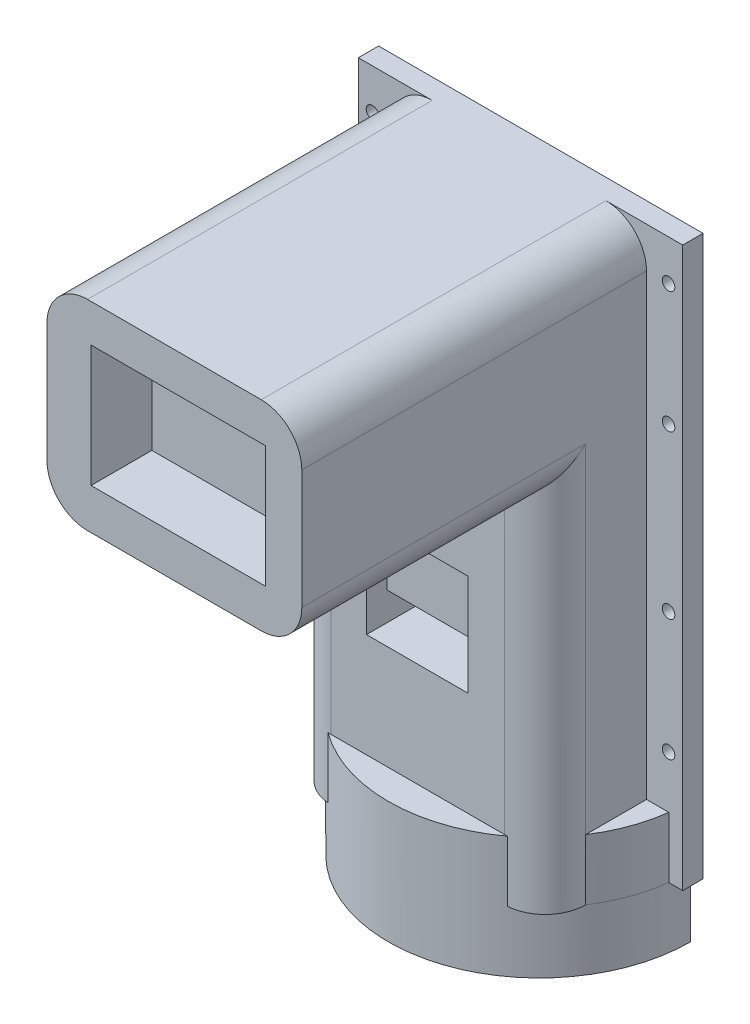
SolidWorks part; units mm, degrees
ref_plane "前视基准面" through (0, 0, 0) normal (0, 0, 1) x (1, 0, 0)
ref_plane "上视基准面" through (0, 0, 0) normal (0, 1, 0) x (1, 0, 0)
ref_plane "右视基准面" through (0, 0, 0) normal (1, 0, 0) x (0, 0, -1)
sketch "草图1" plane through (0, 0, 0) normal (0, 0, 1) x (1, 0, 0)
  line L0 (-49.4413, 51.5796) -> (30.5587, 51.5796)
  line L1 (-49.4413, -104.7842) -> (30.5587, -104.7842)
  line L2 (-49.4413, -104.7842) -> (-49.4413, 51.5796)
  line L4 (30.5587, -104.7842) -> (30.5587, 51.5796)
  point P5 (-15.1842, 61.8107)
  dimension "D2" = 80
extrude "凸台-拉伸1" add sketch "草图1" along normal blind 90
sketch "草图3" plane through (0, 0, 90) normal (0, 0, 1) x (1, 0, 0)
  line L1 (-30.3485, 12.2687) -> (-0.3485, 12.2687)
  line L2 (-30.3485, 12.2687) -> (-30.3485, 42.2687)
  line L3 (-30.3485, 42.2687) -> (-0.3485, 42.2687)
  line L4 (-0.3485, 12.2687) -> (-0.3485, 42.2687)
  dimension "D1" = 30
  dimension "D2" = 30
extrude "切除-拉伸1" cut sketch "草图3" against normal blind 15
sketch "草图4" plane through (0, 0, 90) normal (0, 0, 1) x (1, 0, 0)
  line L5 (-91.0793, 2.1985) -> (91.0793, 2.1985)
  line L6 (-91.0793, 2.1985) -> (-91.0793, -119.1585)
  line L7 (-91.0793, -119.1585) -> (91.0793, -119.1585)
  line L8 (91.0793, 2.1985) -> (91.0793, -119.1585)
  line L9 (0, -119.1585) -> (0, 2.1985) construction
  line L10 (-91.0793, -58.48) -> (91.0793, -58.48) construction
  point P0 (0, -58.48)
extrude "切除-拉伸2" cut sketch "草图4" against normal blind 60
sketch "草图5" plane through (0, 0, 30) normal (0, 0, 1) x (1, 0, 0)
sketch "草图6" plane through (0, 0, 0) normal (0, 0, -1) x (-1, 0, 0)
  line L1 (-15.1234, 38.4096) -> (35.0521, 38.4096)
  line L2 (-15.1234, 38.4096) -> (-15.1234, -110.6371)
  line L3 (-15.1234, -110.6371) -> (35.0521, -110.6371)
  line L4 (35.0521, 38.4096) -> (35.0521, -110.6371)
extrude "切除-拉伸4" cut sketch "草图6" against normal blind 16
sketch "草图7" plane through (0, 0, 90) normal (0, 0, 1) x (1, 0, 0)
  line L1 (-0.3485, 42.2687) -> (12.717, 42.2687)
  line L2 (-0.3485, 42.2687) -> (-0.3485, 12.2687)
  line L3 (-0.3485, 12.2687) -> (12.717, 12.2687)
  line L4 (12.717, 42.2687) -> (12.717, 12.2687)
extrude "切除-拉伸5" cut sketch "草图7" against normal through all
sketch "草图8" plane through (0, 0, 90) normal (0, 0, 1) x (1, 0, 0)
  line L1 (-69.4693, 56.4574) -> (-41.2157, 56.4574)
  line L2 (-69.4693, 56.4574) -> (-69.4693, -112.6205)
  line L3 (-69.4693, -112.6205) -> (-41.2157, -112.6205)
  line L4 (-41.2157, 56.4574) -> (-41.2157, -112.6205)
extrude "切除-拉伸6" cut sketch "草图8" against normal blind 85
sketch "草图10" plane through (0, 0, 30) normal (0, 0, 1) x (1, 0, 0)
  line L1 (-22.43, -45.6106) -> (2.57, -45.6106)
  line L2 (-22.43, -45.6106) -> (-22.43, -20.6106)
  line L3 (-22.43, -20.6106) -> (2.57, -20.6106)
  line L4 (2.57, -45.6106) -> (2.57, -20.6106)
  dimension "D1" = 25
  dimension "D2" = 25
extrude "切除-拉伸7" cut sketch "草图10" against normal blind 5
sketch "草图11" plane through (0, 0, 25) normal (0, 0, 1) x (1, 0, 0)
  line L0 (2.57, -45.6106) -> (2.57, -20.6106) construction
  line L1 (-22.43, -45.6106) -> (2.57, -45.6106)
  line L2 (-22.43, -45.6106) -> (-22.43, -38.5478)
  line L3 (-22.43, -38.5478) -> (2.57, -38.5478)
  line L4 (2.57, -45.6106) -> (2.57, -38.5478)
  dimension "D1" = 7.0628
extrude "切除-拉伸8" cut sketch "草图11" against normal through all
sketch "草图12" plane through (0, 0, 5) normal (0, 0, 1) x (1, 0, 0)
  line L0 (30.5587, 51.5796) -> (-41.2157, 51.5796) construction
  line L1 (30.5587, 2.1985) -> (30.5587, 51.5796) construction
  line L2 (-49.4413, 51.5796) -> (-49.4413, -104.7842) construction
  circle A25 centre (-45.9413, 41.5796) radius 1.5532
  circle A26 centre (27.0587, 41.5796) radius 1.5532
  circle A27 centre (-45.9413, 11.5796) radius 1.5532
  circle A28 centre (-45.9413, -28.4204) radius 1.5532
  circle A29 centre (27.0587, 11.5796) radius 1.5532
  circle A30 centre (27.0587, -28.4204) radius 1.5532
  circle A31 centre (-45.9413, -58.4204) radius 1.5532
  circle A32 centre (27.0587, -58.4204) radius 1.5532
  dimension "D1" = 10
  dimension "D2" = 40
  dimension "D3" = 80
  dimension "D5" = 3.5
  dimension "D4" = 110
  dimension "D6" = 3.5
extrude "切除-拉伸9" cut sketch "草图12" against normal through all
fillet "圆角3" radius 10 1 edges at (-41.2157, -51.2929, 30)
sketch "草图15" plane through (0, 0, 30) normal (0, 0, 1) x (1, 0, 0)
  line L1 (46.77, -108.4786) -> (21.6228, -108.4786)
  line L2 (46.77, -108.4786) -> (46.77, 63.4099)
  line L3 (46.77, 63.4099) -> (21.6228, 63.4099)
  line L4 (21.6228, -108.4786) -> (21.6228, 63.4099)
extrude "切除-拉伸10" cut sketch "草图15" against normal blind 85 from surface at 60 starting at face at (-8.8157, 27.2687, 90)
fillet "圆角6" radius 10 1 edges at (21.6228, -51.2929, 30)
fillet "圆角7" radius 10 4 edges at (21.6228, 2.1985, 55) (-41.2157, 2.1985, 55) (-41.2157, 51.5796, 47.5) (21.6228, 51.5796, 47.5)
sketch "草图18" plane through (0, 0, 0) normal (0, 0, -1) x (-1, 0, 0)
  line L1 (-56.1882, -118.8722) -> (96.1605, -118.8722)
  line L2 (-56.1882, -118.8722) -> (-56.1882, -86.2935)
  line L3 (-56.1882, -86.2935) -> (96.1605, -86.2935)
  line L4 (96.1605, -118.8722) -> (96.1605, -86.2935)
extrude "切除-拉伸11" cut sketch "草图18" against normal through all
sketch "草图19" plane through (0, -86.2935, 0) normal (0, -1, 0) x (1, 0, 0)
  line L0 (-9.7964, 30) -> (-9.7964, -5.6173) construction
  line L1 (11.6228, 30) -> (-31.2157, 30) construction
  line L2 (-35.0521, 0) -> (-0.3485, 0) construction
  circle A0 centre (-9.7964, 0) radius 32.5
  circle A1 centre (-9.7964, 0) radius 37.2544
  dimension "D1" = 65
extrude "凸台-拉伸3" add sketch "草图19" along normal blind 15
sketch "草图20" plane through (0, -101.2935, 0) normal (0, -1, 0) x (1, 0, 0)
  line L5 (-68.9122, -42.5484) -> (58.8177, -42.5484)
  line L6 (-68.9122, -42.5484) -> (-68.9122, 0)
  line L7 (-68.9122, 0) -> (58.8177, 0)
  line L8 (58.8177, -42.5484) -> (58.8177, 0)
extrude "切除-拉伸12" cut sketch "草图20" against normal through all
sketch "草图24" plane through (0, -86.2935, 0) normal (0, 1, 0) x (1, 0, 0)
  line L0 (-46.7138, -5) -> (-41.2157, -5)
  line L1 (-41.2157, -90) -> (-41.2157, -5) construction
  line L2 (-31.2157, -5) -> (-49.4413, -5) construction
  line L3 (-41.2157, -20) -> (-41.2157, -5)
  arc A0 (-46.7138, -5) -> (-41.2157, -20) centre (-7.4884, 0.87) ccw
extrude "凸台-拉伸5" add sketch "草图24" along normal blind 15
sketch "草图25" plane through (0, -86.2935, 0) normal (0, 1, 0) x (1, 0, 0)
  line L0 (-31.9182, -29.9753) -> (12.3253, -29.9753)
  arc A0 (-31.9182, -29.9753) -> (12.3253, -29.9753) centre (-9.7964, 0) ccw
extrude "凸台-拉伸6" add sketch "草图25" along normal blind 15
sketch "草图26" plane through (0, -86.2935, 0) normal (0, 1, 0) x (1, 0, 0)
  line L0 (27.1209, -5) -> (21.6228, -5)
  line L1 (21.6228, -5) -> (21.6228, -90) construction
  line L2 (30.5587, -5) -> (11.6228, -5) construction
  line L3 (21.6228, -20) -> (21.6228, -5)
  arc A0 (27.1209, -5) -> (21.6228, -20) centre (-7.8422, -0.6923) cw
extrude "凸台-拉伸7" add sketch "草图26" along normal blind 15
sketch "草图27" plane through (0, 0, 25) normal (0, 0, 1) x (1, 0, 0)
  circle A0 centre (-4.6757, -23.9548) radius 1.5
  circle A1 centre (-14.6757, -23.9548) radius 1.5
  point P4 (-4.6757, -23.9548)
  dimension "D1" = 3
  dimension "D2" = 3
  dimension "D3" = 10
extrude "切除-拉伸13" cut sketch "草图27" against normal blind 10
